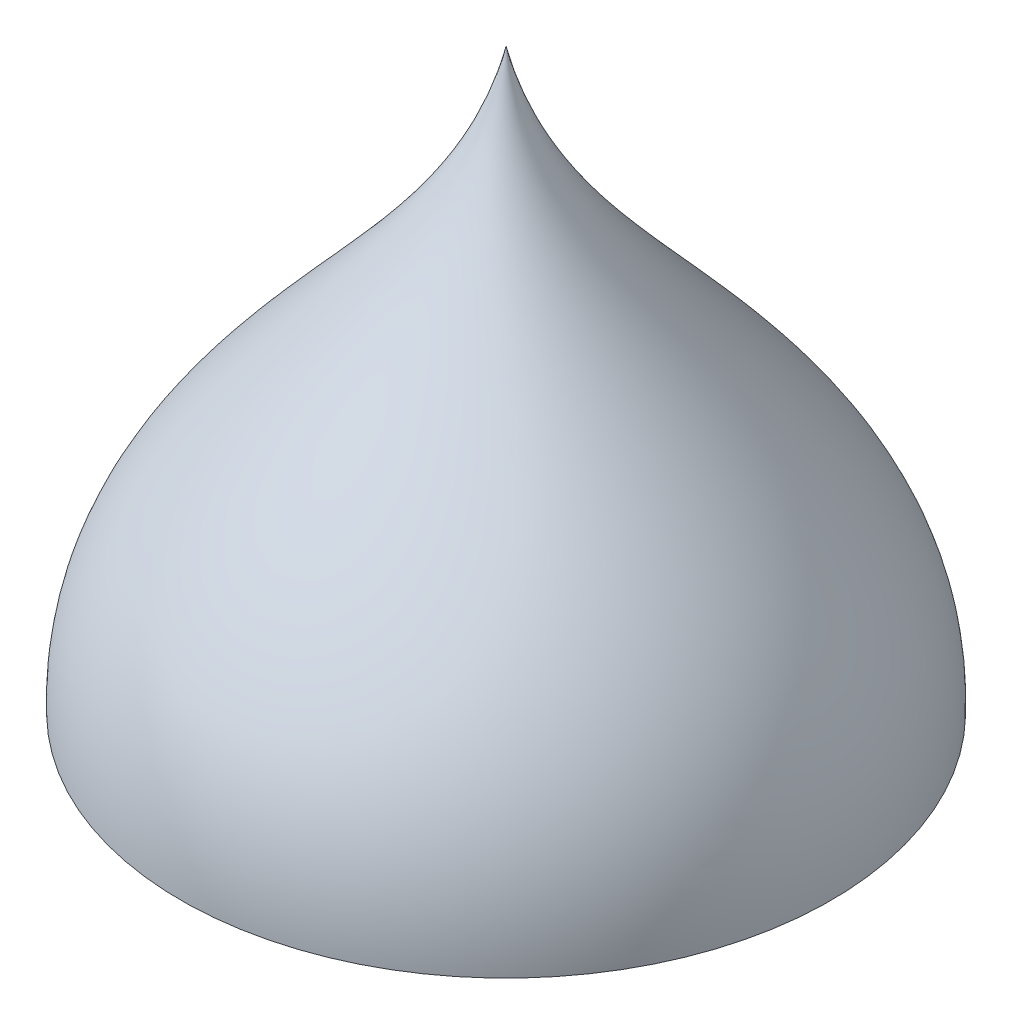
SolidWorks part; units mm, degrees
ref_plane "Front Plane" through (0, 0, 0) normal (0, 0, 1) x (1, 0, 0)
ref_plane "Top Plane" through (0, 0, 0) normal (0, 1, 0) x (1, 0, 0)
ref_plane "Right Plane" through (0, 0, 0) normal (1, 0, 0) x (0, 0, -1)
sketch "Sketch1" plane through (0, 0, 0) normal (0, 0, 1) x (1, 0, 0)
  line L0 (0, 0) -> (0, 8) construction
  line L1 (0, 8) -> (-4.5, 0) construction
  line L2 (-4.5, 0) -> (-3.1, 0)
  line L3 (-2, 1) -> (-2, 0)
  line L4 (-2, 0) -> (0, 0)
  line L5 (0, 0) -> (0, 8)
  line L6 (-3.1, 0) -> (-3.1, 1)
  line L7 (-3.1, 1) -> (-2, 1)
  spline S0 degree 3 poles (-4.5, 0) (-4.6122, 3.3833) (-0.6968, 4.89) (0, 8) knots 0 0 0 0 1 1 1 1
  dimension "D1" = 8
  dimension "D2" = 4.5
  dimension "D3" = 3.1
  dimension "D4" = 2
  dimension "D5" = 1
revolve "Revolve1" add sketch "Sketch1" angle 360 about L5
